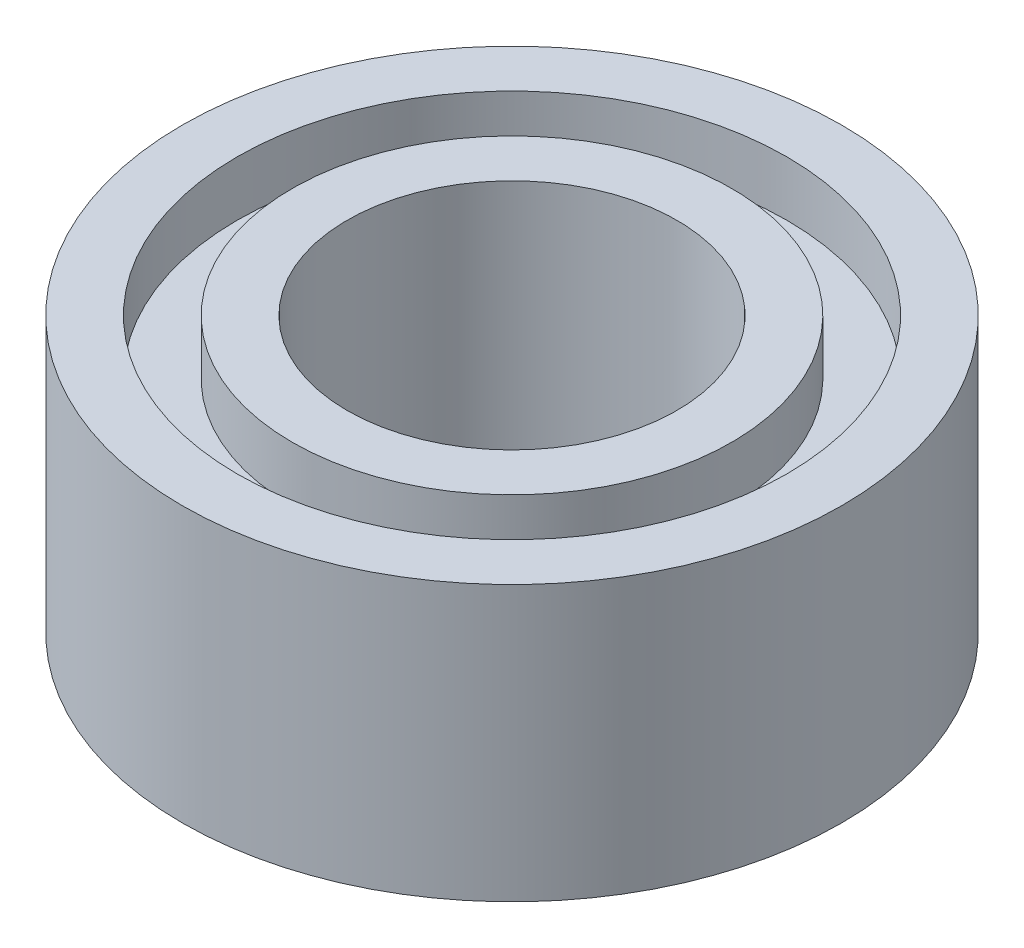
SolidWorks part; units mm, degrees
ref_plane "前视基准面" through (0, 0, 0) normal (0, 0, 1) x (1, 0, 0)
ref_plane "上视基准面" through (0, 0, 0) normal (0, 1, 0) x (1, 0, 0)
ref_plane "右视基准面" through (0, 0, 0) normal (1, 0, 0) x (0, 0, -1)
sketch "草图1" plane through (0, 0, 0) normal (0, 1, 0) x (1, 0, 0)
  circle A0 centre (0, 0) radius 3
  circle A1 centre (0, 0) radius 1.5
  dimension "D1" = 6
  dimension "D2" = 3
extrude "凸台-拉伸1" add sketch "草图1" along normal blind 2.5
sketch "草图2" plane through (0, 2.5, 0) normal (0, 1, 0) x (1, 0, 0)
  circle A0 centre (0, 0) radius 2
  circle A1 centre (0, 0) radius 2.5
  dimension "D1" = 5
  dimension "D2" = 4
extrude "切除-拉伸1" cut sketch "草图2" against normal blind 0.5
sketch "草图3" plane through (0, 0, 0) normal (0, -1, 0) x (1, 0, 0)
  circle A0 centre (0, 0) radius 2.5
  circle A1 centre (0, 0) radius 2
  dimension "D1" = 5
  dimension "D2" = 4
extrude "切除-拉伸2" cut sketch "草图3" against normal blind 0.5
